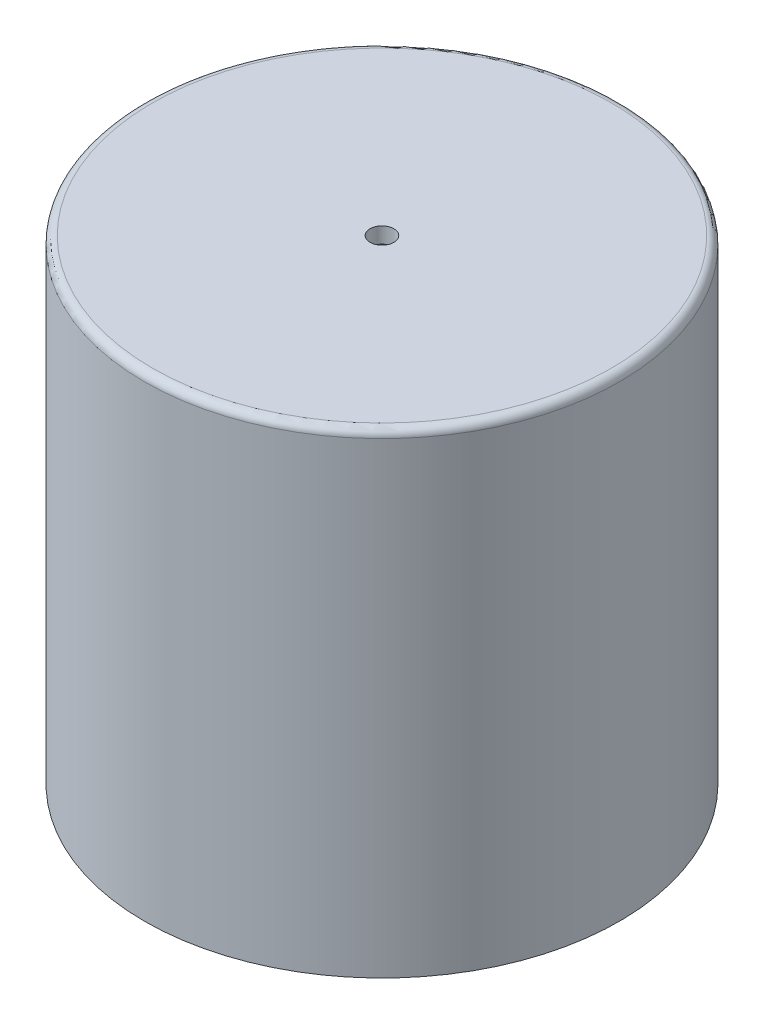
SolidWorks part; units mm, degrees
ref_plane "Front Plane" through (0, 0, 0) normal (0, 0, 1) x (1, 0, 0)
ref_plane "Top Plane" through (0, 0, 0) normal (0, 1, 0) x (1, 0, 0)
ref_plane "Right Plane" through (0, 0, 0) normal (1, 0, 0) x (0, 0, -1)
sketch "Sketch1" plane through (0, 0, 0) normal (0, 1, 0) x (1, 0, 0)
  circle A0 centre (0, 0) radius 30
  dimension "D1" = 60
extrude "Boss-Extrude1" add sketch "Sketch1" along normal blind 60
sketch "Sketch2" plane through (0, 0, 0) normal (0, -1, 0) x (-1, 0, 0)
  circle A0 centre (0, 0) radius 28.4
  circle A1 centre (0, 0) radius 30 construction
  dimension "D1" = 1.6
extrude "Cut-Extrude1" cut sketch "Sketch2" against normal blind 58
sketch "Sketch3" plane through (0, 60, 0) normal (0, 1, 0) x (1, 0, 0)
  circle A0 centre (0, 0) radius 1.5
  dimension "D1" = 3
extrude "Cut-Extrude2" cut sketch "Sketch3" against normal up to surface (2 mm away) up to face at (0, 58, -28.4)
fillet "Fillet2" radius 1 1 edges at (0, 58, -28.4)
fillet "Fillet3" radius 1 1 edges at (0, 60, 30)
